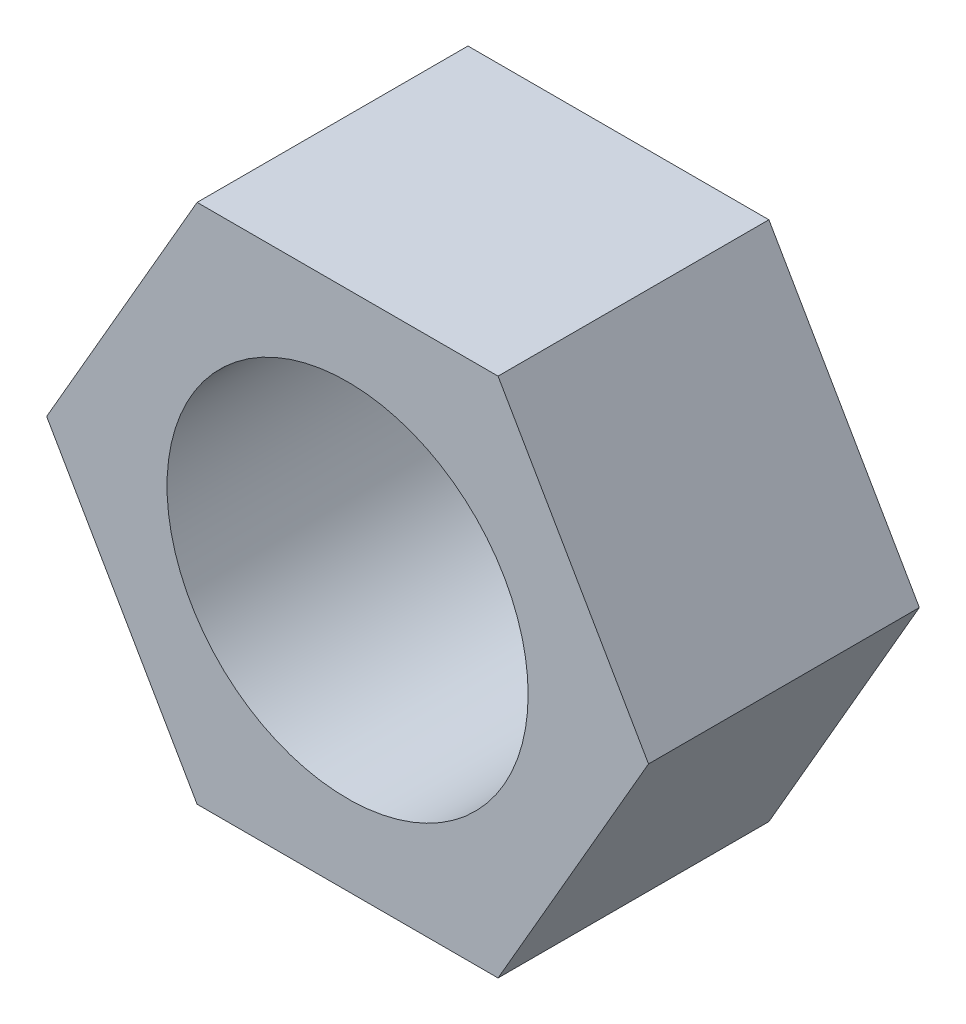
SolidWorks part; units mm, degrees
ref_plane "Front Plane" through (0, 0, 0) normal (0, 0, 1) x (1, 0, 0)
ref_plane "Top Plane" through (0, 0, 0) normal (0, 1, 0) x (1, 0, 0)
ref_plane "Right Plane" through (0, 0, 0) normal (1, 0, 0) x (0, 0, -1)
sketch "Sketch1" plane through (0, 0, 0) normal (0, 0, 1) x (1, 0, 0)
  line L1 (10, 17.3205) -> (-10, 17.3205)
  line L2 (-10, 17.3205) -> (-20, 0)
  line L3 (-20, 0) -> (-10, -17.3205)
  line L4 (-10, -17.3205) -> (10, -17.3205)
  line L5 (10, -17.3205) -> (20, 0)
  line L6 (20, 0) -> (10, 17.3205)
  circle A0 centre (0, 0) radius 17.3205 construction
  circle A1 centre (0, 0) radius 12
  dimension "D2" = 24
  dimension "D1" = 20
extrude "Boss-Extrude1" add sketch "Sketch1" along normal mid plane 18
